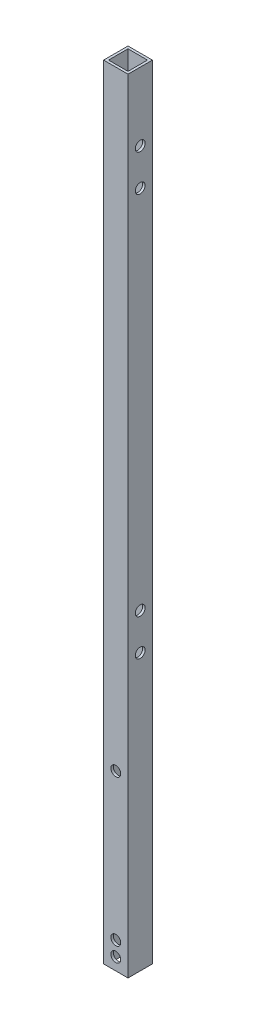
SolidWorks part; units mm, degrees
material "1345 Alloy"
ref_plane "Front Plane" through (0, 0, 0) normal (0, 0, 1) x (1, 0, 0)
ref_plane "Top Plane" through (0, 0, 0) normal (0, 1, 0) x (1, 0, 0)
ref_plane "Right Plane" through (0, 0, 0) normal (1, 0, 0) x (0, 0, -1)
sketch "Sketch1" plane through (0, 0, 0) normal (0, 1, 0) x (1, 0, 0)
  line L1 (-5, 5) -> (5, 5)
  line L2 (-5, 5) -> (-5, -5)
  line L3 (-5, -5) -> (5, -5)
  line L4 (5, 5) -> (5, -5)
  line L5 (-5, 5) -> (5, -5) construction
  line L6 (-5, -5) -> (5, 5) construction
  line L7 (-4, 4) -> (4, 4)
  line L8 (-4, 4) -> (-4, -4)
  line L9 (-4, -4) -> (4, -4)
  line L10 (4, 4) -> (4, -4)
  line L11 (-4, 4) -> (4, -4) construction
  line L12 (-4, -4) -> (4, 4) construction
  point P0 (0, 0)
  point P6 (0, 0)
  dimension "D1" = 10
  dimension "D2" = 10
  dimension "D3" = 8
  dimension "D4" = 8
extrude "Boss-Extrude1" add sketch "Sketch1" along normal blind 340
sketch "Sketch2" plane through (0, 0, 5) normal (0, 0, 1) x (1, 0, 0)
  line L0 (0, 0) -> (0, 308.5407) construction
  line L2 (-5, 340) -> (5, 340) construction
  circle A0 centre (0, 90) radius 2.025
  circle A1 centre (0, 30) radius 2.025
  circle A2 centre (0, 24) radius 2.025
  circle A6 centre (0, 18) radius 2.025 [skipped]
  circle A7 centre (0, 12) radius 2.025 [skipped]
  circle A8 centre (0, 6) radius 2.025 [skipped]
  dimension "D1" = 4.05
  dimension "D3" = 4.05
  dimension "D2" = 250
  dimension "D4" = 310
  dimension "D6" = 6
  dimension "D5" = 5
extrude "Cut-Extrude1" cut sketch "Sketch2" against normal through all
sketch "Sketch3" plane through (5, 0, 0) normal (1, 0, 0) x (0, 0, -1)
  line L0 (0, 330.8461) -> (0, -19.7241) construction
  line L2 (-5, 0) -> (5, 0) construction
  circle A0 centre (0, 312) radius 2.028
  circle A1 centre (0, 297) radius 2.025
  circle A2 centre (0, 147) radius 2.025
  circle A3 centre (0, 132) radius 2.025
  dimension "D1" = 4.056
  dimension "D2" = 4.05
  dimension "D5" = 4.05
  dimension "D6" = 4.05
  dimension "D3" = 132
  dimension "D4" = 15
  dimension "D7" = 15
  dimension "D8" = 150
extrude "Cut-Extrude2" cut sketch "Sketch3" against normal through all
sketch "Sketch4" plane through (0, 0, 5) normal (0, 0, 1) x (1, 0, 0)
  line L0 (-5, 19) -> (5, 19)
  line L1 (-5, 340) -> (-5, 0) construction
  line L2 (5, 340) -> (5, 0) construction
  line L3 (5, 19) -> (5, 0)
  line L4 (5, 0) -> (-5, 0)
  line L5 (-5, 0) -> (-5, 19)
  line L6 (0, 24) -> (-8.927, 24) construction
  dimension "D1" = 5
extrude "Cut-Extrude3" cut sketch "Sketch4" against normal through all
